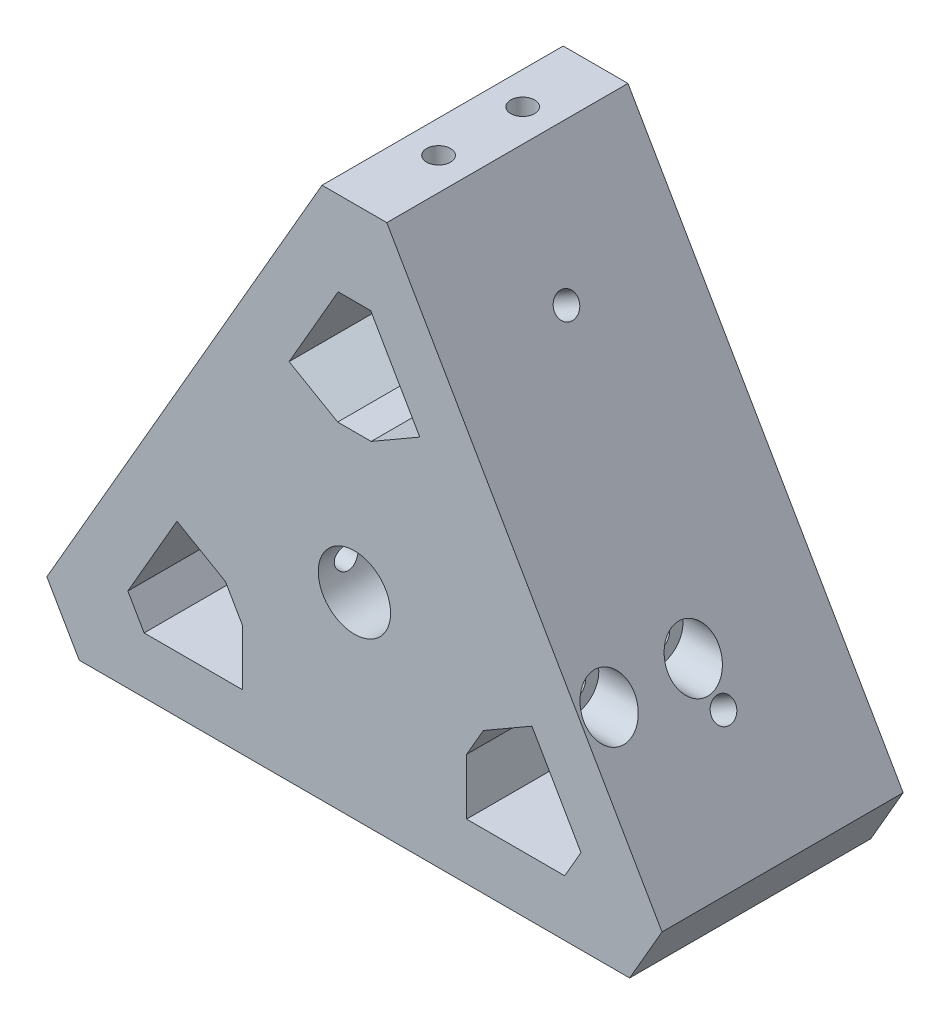
SolidWorks part; units mm, degrees
material "PLA"
ref_plane "前视基准面" through (0, 0, 0) normal (0, 0, 1) x (1, 0, 0)
ref_plane "上视基准面" through (0, 0, 0) normal (0, 1, 0) x (1, 0, 0)
ref_plane "右视基准面" through (0, 0, 0) normal (1, 0, 0) x (0, 0, -1)
other "Configuration Table"
sketch "草图1" plane through (0, 0, 0) normal (0, 0, 1) x (1, 0, 0)
  line L0 (0, 70) -> (-60.6218, -35)
  line L5 (-60.6218, -35) -> (60.6218, -35)
  line L6 (60.6218, -35) -> (0, 70)
  line L11 (0, 0) -> (0, 42.5867) construction
  line L13 (0, 0) -> (0, -35) construction
  line L14 (0, 0) -> (30.3109, 17.5) construction
  line L15 (-5.7735, 60) -> (5.7735, 60)
  line L16 (54.8483, -25) -> (49.0748, -35)
  line L17 (-49.0748, -35) -> (-54.8483, -25)
  circle A1 centre (0, 0) radius 6.45
  point P9 (-47.498, -48.1205)
  point P11 (0, 0)
  point P18 (0, 0)
  dimension "D5" = 3
  dimension "D1" = 12.9
  dimension "D2" = 60
  dimension "D3" = 35
  dimension "D4" = 10
extrude "凸台-拉伸1" add sketch "草图1" along normal blind 43 contours L17 L5 L16 L6 L15 L0 A1
sketch "草图2" plane through (0, 0, 43) normal (0, 0, 1) x (1, 0, 0)
  line L0 (-2.9006, 44.976) -> (5.7596, 39.976)
  line L1 (5.7596, 39.976) -> (-31.7404, -24.976)
  line L2 (-5.7735, 60) -> (-54.8483, -25) construction
  line L3 (0, 0) -> (-68.0781, 39.3049) construction
  line L4 (-40.4006, -19.976) -> (-31.7404, -24.976)
  line L5 (-40.4006, -19.976) -> (-2.9006, 44.976)
  line L6 (40.4006, -19.976) -> (31.7404, -24.976)
  line L7 (31.7404, -24.976) -> (-5.7596, 39.976)
  line L8 (2.9006, 44.976) -> (-5.7596, 39.976)
  line L9 (2.9006, 44.976) -> (40.4006, -19.976)
  line L10 (-37.5, -25) -> (-37.5, -15)
  line L11 (-37.5, -15) -> (37.5, -15)
  line L12 (37.5, -25) -> (37.5, -15)
  line L13 (37.5, -25) -> (-37.5, -25)
  line L14 (-2.9904, 24.8205) -> (-11.6506, 29.8205)
  line L15 (-22.9904, -9.8205) -> (-31.6506, -4.8205)
  line L16 (22.9904, -9.8205) -> (31.6506, -4.8205)
  line L17 (2.9904, 24.8205) -> (11.6506, 29.8205)
  line L18 (-20, -15) -> (-20, -25)
  line L19 (20, -15) -> (20, -25)
  line L20 (-2.9006, 44.976) -> (2.9006, 44.976)
  line L21 (-40.4006, -19.976) -> (-37.5, -25)
  line L22 (40.4006, -19.976) -> (37.5, -25)
  line L23 (-22.9904, -9.8205) -> (-20, -15)
  line L24 (22.9904, -9.8205) -> (20, -15)
  line L25 (2.9904, 24.8205) -> (-2.9904, 24.8205)
  point P19 (0, 0)
  point P33 (0, 0)
  dimension "D1" = 75
  dimension "D2" = 10
  dimension "D3" = 10
  dimension "D5" = 40
  dimension "D4" = 3
  dimension "D6" = 3
extrude "切除-拉伸3" cut sketch "草图2" against normal through all contours L0 L8 L7 L1 | L14 L1 L7 L8 L0 L5 | L7 L17 L9 L8 L0 L1 | L1 L15 L5 L4 L10 L11 | L11 L10 L4 L1 | L18 L11 L1 L4 L10 L13 | L11 L19 L13 L12 L6 L7 | L6 L12 L11 L7 | L16 L7 L11 L12 L6 L9 | L20 L0 L8 | L4 L21 L10 | L22 L6 L12 | L7 L24 L11 | L23 L1 L11 | L25 L7 L1
sketch "草图3" plane through (-30.3109, 17.5, 0) normal (-0.866, 0.5, 0) x (0, 0, 1)
  line L0 (0, 0) -> (67.8776, 0) construction
  line L1 (0, 49.0748) -> (0, -49.0748) construction
  line L2 (43, 54.8483) -> (0, 54.8483) construction
  circle A0 centre (21.5, 28) radius 2.125
  circle A2 centre (21.5, -28) radius 2.125
  point P10 (21.5, 54.8483)
  dimension "D1" = 56
  dimension "D2" = 4.25
extrude "切除-拉伸4" cut sketch "草图3" against normal blind 15
pattern_circular "阵列(圆周)1" count 3 over 360 about axis through (0, 0, 43) along (0, 0, -1) of "切除-拉伸4"
sketch "草图4" plane through (0, -35, 0) normal (0, -1, 0) x (1, 0, 0)
  line L0 (-49.0748, 0) -> (49.0748, 0) construction
  circle A0 centre (0, 13) radius 2.125
  circle A1 centre (0, 28) radius 2.125
  point P6 (0, 0)
  dimension "D1" = 13
  dimension "D2" = 15
  dimension "D3" = 4.25
extrude "切除-拉伸5" cut sketch "草图4" against normal through all
ref_plane "基准面1" through (49.0748, 0, 0) normal (-1, 0, 0) x (0, 0, -1)
sketch "草图6" plane through (49.0748, 0, 0) normal (-1, 0, 0) x (0, 0, -1)
  line L5 (0, 25) -> (0, -60) construction
  line L6 (-21.5, 35) -> (-21.5, -35) construction
  line L7 (-43, 35) -> (0, 35) construction
  circle A0 centre (-23, 0) radius 2.15
  circle A1 centre (-38, 0) radius 2.15
  point P4 (-23, -12.5193)
  point P5 (-23, -23.8745)
  point P6 (-36.217, -5.0528)
  point P7 (-21.5, 0)
  point P8 (-36.7111, 0)
  dimension "D1" = 15
  dimension "D2" = 70
  dimension "D3" = 4.3
  dimension "D4" = 23
extrude "切除-拉伸7" cut sketch "草图6" along normal through all
sketch "草图7" plane through (49.0748, 0, 0) normal (-1, 0, 0) x (0, 0, -1)
  circle A0 centre (-38, 0) radius 4.5
  circle A1 centre (-23, 0) radius 4.5
  dimension "D1" = 9
  dimension "D2" = 9
extrude "切除-拉伸8" cut sketch "草图7" along normal blind 15
